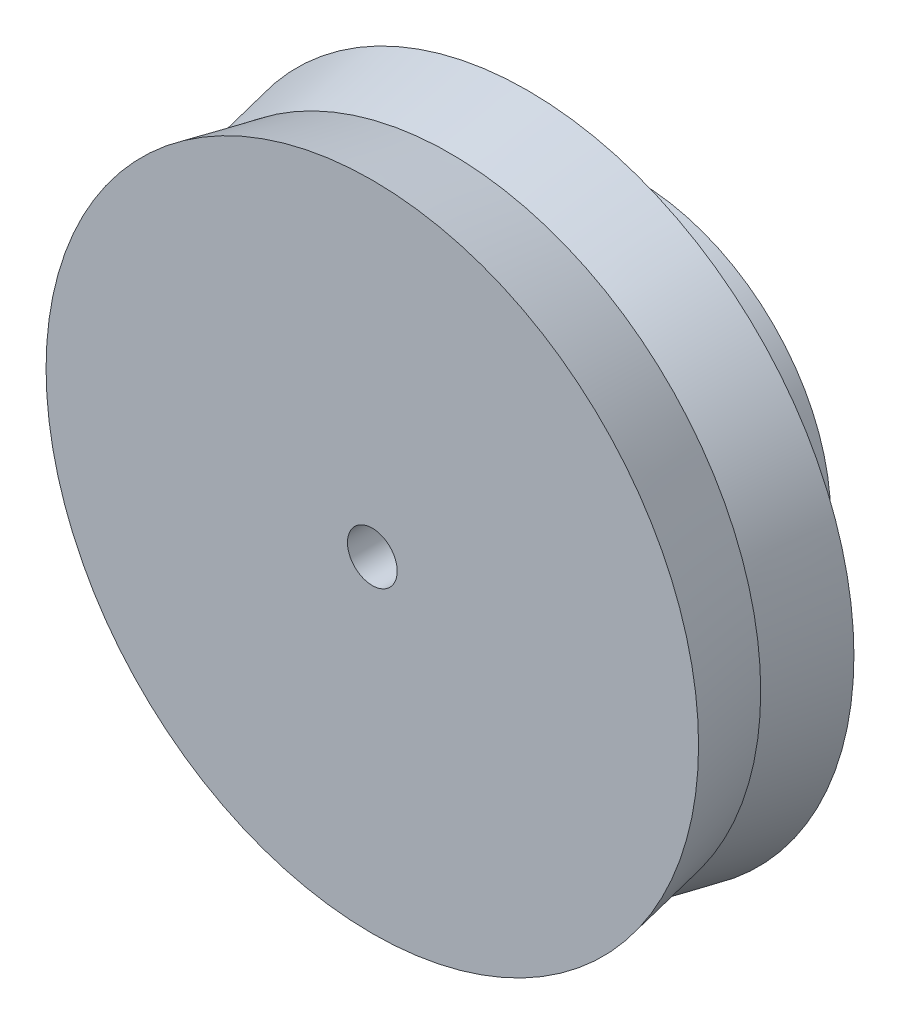
SolidWorks part; units mm, degrees
ref_plane "Front Plane" through (0, 0, 0) normal (0, 0, 1) x (1, 0, 0)
ref_plane "Top Plane" through (0, 0, 0) normal (0, 1, 0) x (1, 0, 0)
ref_plane "Right Plane" through (0, 0, 0) normal (1, 0, 0) x (0, 0, -1)
sketch "Sketch2" plane through (0, 0, 0) normal (0, 1, 0) x (1, 0, 0)
  line L0 (0, 5) -> (0, -5)
  line L1 (0, 5) -> (21, 5)
  line L2 (0, -5) -> (21, -5)
  line L3 (0, 0) -> (20, 0) construction
  line L4 (21, 5) -> (20, 0)
  line L5 (20, 0) -> (21, -5)
  point P4 (0, 0)
  point P9 (0, 0)
  dimension "D3" = 21
  dimension "D1" = 10
  dimension "D2" = 20
revolve "Revolve1" add sketch "Sketch2" angle 360 about L0
sketch "Sketch4" plane through (0, 0, -5) normal (0, 0, -1) x (-1, 0, 0)
  circle A0 centre (0, 0) radius 12.5
  dimension "D1" = 25
extrude "Boss-Extrude1" add sketch "Sketch4" along normal blind 7
sketch "Sketch3" plane through (0, 0, -5) normal (0, 0, -1) x (-1, 0, 0)
  circle A0 centre (0, 0) radius 1.6
  dimension "D1" = 3.2
extrude "Cut-Extrude1" cut sketch "Sketch3" against normal through all both and the other way through all
sketch "Sketch5" plane through (0, 0, 0) normal (1, 0, 0) x (0, 0, -1)
  line L0 (5, 0) -> (12, 0) construction
  line L2 (12, -12.5) -> (12, 12.5) construction
  line L3 (5, -12.5) -> (5, 12.5) construction
  line L4 (5, -12.5) -> (5, 12.5) construction
  circle A0 centre (8.5, 0) radius 1.65
  point P2 (0, 0)
  point P5 (6.1781, 0)
  point P10 (8.5, 0)
  point P11 (5, 0)
  dimension "D1" = 3.3
extrude "Cut-Extrude2" cut sketch "Sketch5" against normal through all both and the other way through all
ref_plane "Plane1" through (-3.2, 0, 0) normal (1, 0, 0) x (0, 0, -1)
sketch "Sketch6" plane through (-3.2, 0, 0) normal (1, 0, 0) x (0, 0, -1)
  line L0 (10.1454, 2.85) -> (12, 2.85)
  line L1 (6.8546, -2.85) -> (10.1454, -2.85)
  line L2 (10.1454, -2.85) -> (11.7909, 0) construction
  line L3 (11.7909, 0) -> (10.1454, 2.85) construction
  line L4 (10.1454, 2.85) -> (6.8546, 2.85)
  line L5 (6.8546, 2.85) -> (5.2091, 0)
  line L6 (5.2091, 0) -> (6.8546, -2.85)
  line L7 (12, -12.5) -> (12, 12.5) construction
  line L8 (12, 2.85) -> (12, -2.85)
  line L9 (12, -2.85) -> (10.1454, -2.85)
  circle A0 centre (8.5, 0) radius 2.85 construction
  dimension "D1" = 5.7
extrude "Cut-Extrude3" cut sketch "Sketch6" against normal blind 2.7
ref_plane "Plane2" through (3.2, 0, 0) normal (1, 0, 0) x (0, 0, -1)
sketch "Sketch7" plane through (3.2, 0, 0) normal (1, 0, 0) x (0, 0, -1)
  line L7 (12, 2.85) -> (10.1454, 2.85)
  line L8 (12, -2.85) -> (12, 2.85)
  line L9 (10.1454, -2.85) -> (12, -2.85)
  line L10 (6.8546, -2.85) -> (10.1454, -2.85)
  line L11 (5.2091, 0) -> (6.8546, -2.85)
  line L12 (6.8546, 2.85) -> (5.2091, 0)
  line L13 (10.1454, 2.85) -> (6.8546, 2.85)
  line L14 (12, 2.85) -> (10.1454, 2.85)
  line L15 (12, -2.85) -> (12, 2.85)
  line L16 (10.1454, -2.85) -> (12, -2.85)
  line L17 (6.8546, -2.85) -> (10.1454, -2.85)
  line L18 (5.2091, 0) -> (6.8546, -2.85)
  line L19 (6.8546, 2.85) -> (5.2091, 0)
  line L20 (10.1454, 2.85) -> (6.8546, 2.85)
  dimension "D1" = 0
extrude "Cut-Extrude4" cut sketch "Sketch7" along normal blind 2.7
